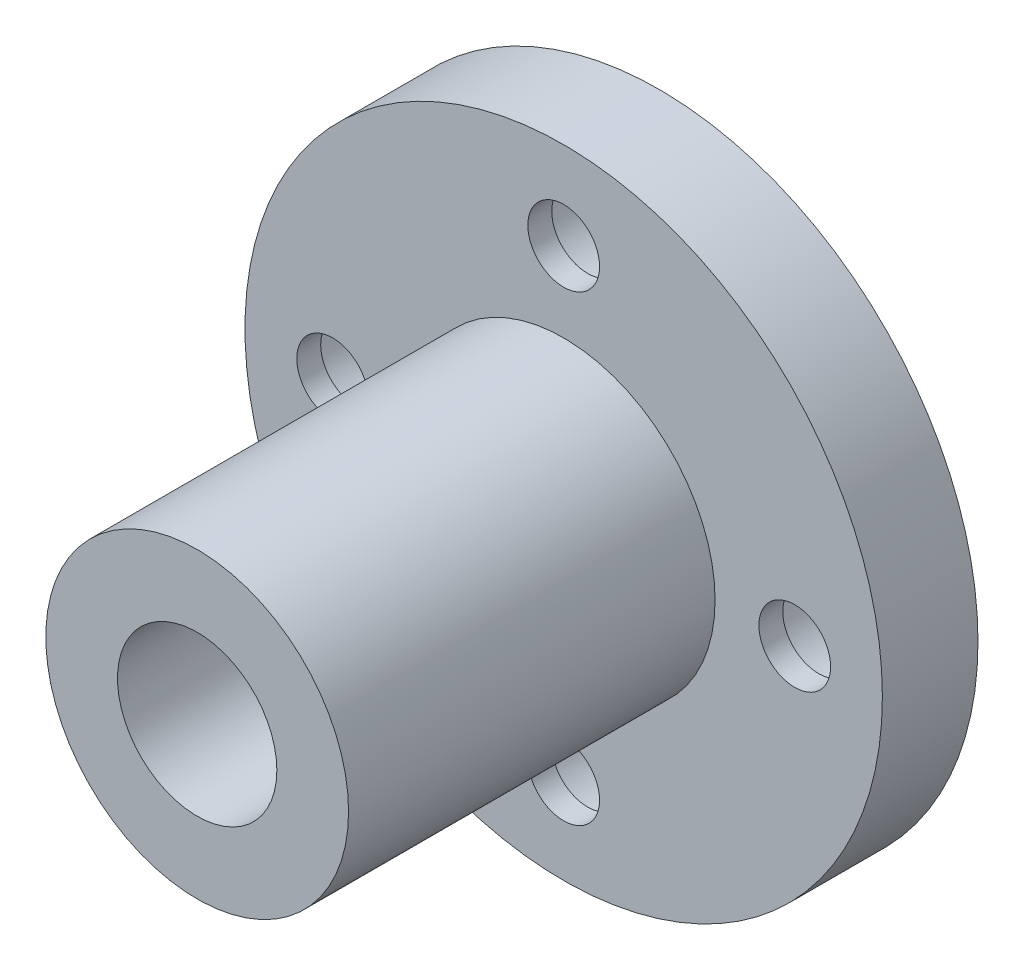
SolidWorks part; units mm, degrees
ref_plane "Спереди" through (0, 0, 0) normal (0, 0, 1) x (1, 0, 0)
ref_plane "Сверху" through (0, 0, 0) normal (0, 1, 0) x (1, 0, 0)
ref_plane "Справа" through (0, 0, 0) normal (1, 0, 0) x (0, 0, -1)
sketch "Эскиз1" plane through (0, 0, 0) normal (0, 0, 1) x (1, 0, 0)
  line L0 (0, 20) -> (0, -20) construction
  line L1 (-20, 0) -> (20, 0) construction
  circle A0 centre (0, 0) radius 20
  circle A1 centre (0, 0) radius 5
  circle A2 centre (0, 0) radius 14.5 construction
  circle A3 centre (0, 14.5) radius 2.25
  circle A4 centre (14.5, 0) radius 2.25
  circle A5 centre (0, -14.5) radius 2.25
  circle A6 centre (-14.5, 0) radius 2.25
  point P17 (0, 0)
  point P18 (-14.5, 0)
  point P19 (14.5, 0)
  dimension "D1" = 40
  dimension "D2" = 10
  dimension "D3" = 29
  dimension "D4" = 4.5
extrude "Бобышка-Вытянуть1" add sketch "Эскиз1" along normal blind 6
sketch "Эскиз2" plane through (0, 0, 6) normal (0, 0, 1) x (1, 0, 0)
  circle A0 centre (0, 0) radius 9.5
  circle A1 centre (0, 0) radius 5 construction
  circle A2 centre (0, 0) radius 5
  dimension "D1" = 19
extrude "Бобышка-Вытянуть2" add sketch "Эскиз2" along normal blind 23
sketch "Эскиз3" plane through (0, 0, 0) normal (0, 0, -1) x (-1, 0, 0)
  circle A0 centre (0, 14.5) radius 3.75
  circle A1 centre (14.5, 0) radius 3.75
  circle A2 centre (0, -14.5) radius 3.75
  circle A3 centre (-14.5, 0) radius 3.75
  dimension "D1" = 7.5
extrude "Вырез-Вытянуть1" cut sketch "Эскиз3" against normal blind 4.5
